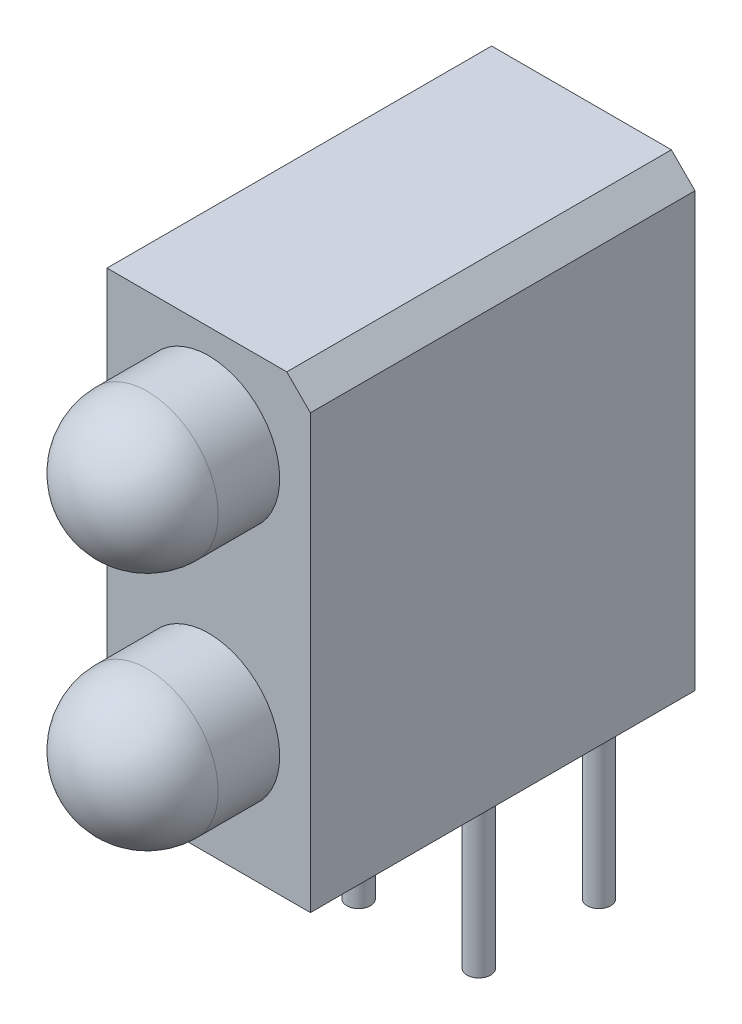
SolidWorks part; units mm, degrees
ref_plane "Plan de face" through (0, 0, 0) normal (0, 0, 1) x (1, 0, 0)
ref_plane "Plan de dessus" through (0, 0, 0) normal (0, 1, 0) x (1, 0, 0)
ref_plane "Plan de droite" through (0, 0, 0) normal (1, 0, 0) x (0, 0, -1)
sketch "Esquisse1" plane through (0, 0, 0) normal (0, 0, 1) x (1, 0, 0)
  line L0 (0, 0) -> (0, 9.4049) construction
  line L2 (-2.15, 0) -> (2.15, 0)
  line L3 (-2.15, 0) -> (-2.15, 9.65)
  line L4 (-2.15, 9.65) -> (2.15, 9.65)
  line L5 (2.15, 0) -> (2.15, 9.65)
  dimension "D1" = 9.65
  dimension "D2" = 4.3
extrude "Boss.-Extru.1" add sketch "Esquisse1" along normal blind 8.13
sketch "Esquisse2" plane through (0, 0, 8.13) normal (0, 0, 1) x (1, 0, 0)
  line L0 (-2.15, 0) -> (2.15, 0) construction
  circle A0 centre (0, 7.62) radius 1.5
  circle A1 centre (0, 2.54) radius 1.5
  dimension "D1" = 3
  dimension "D2" = 3
  dimension "D3" = 2.54
  dimension "D4" = 5.08
extrude "Boss.-Extru.2" add sketch "Esquisse2" along normal blind 2.8 separate body
fillet "Congé1" radius 1.5 1 edges at (1.5, 7.62, 10.93)
fillet "Congé2" radius 1.5 1 edges at (1.5, 2.54, 10.93)
chamfer "Chanfrein1" distance 0.5 angle 45 1 edges at (2.15, 9.65, 4.065)
sketch "Esquisse3" plane through (0, 0, 0) normal (0, -1, 0) x (1, 0, 0)
  line L0 (0, 0) -> (0, 11.5849) construction
  line L1 (-2.15, 8.13) -> (2.15, 8.13) construction
  circle A0 centre (-1.27, 3.69) radius 0.25
  circle A1 centre (1.27, 3.69) radius 0.25
  circle A2 centre (-1.27, 1.15) radius 0.25
  circle A3 centre (1.27, 1.15) radius 0.25
  dimension "D1" = 0.5
  dimension "D2" = 1.27
  dimension "D3" = 4.44
  dimension "D4" = 2
extrude "Boss.-Extru.3" add sketch "Esquisse3" along normal blind 3.68
